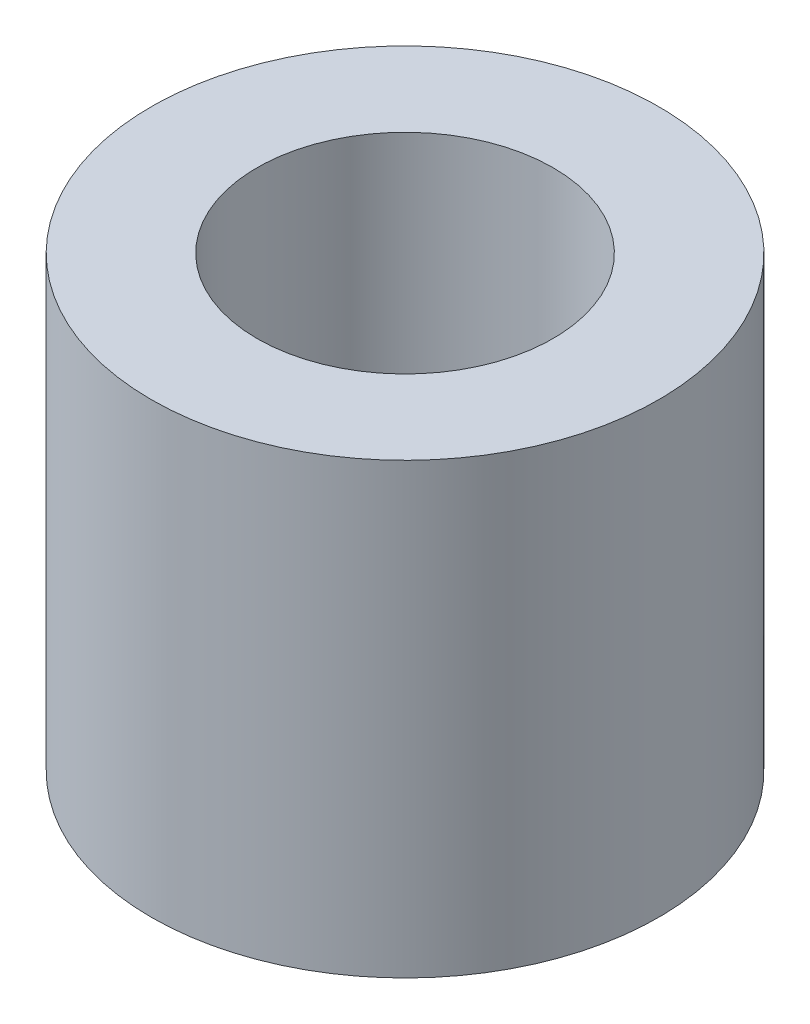
SolidWorks part; units mm, degrees
ref_plane "前视基准面" through (0, 0, 0) normal (0, 0, 1) x (1, 0, 0)
ref_plane "上视基准面" through (0, 0, 0) normal (0, 1, 0) x (1, 0, 0)
ref_plane "右视基准面" through (0, 0, 0) normal (1, 0, 0) x (0, 0, -1)
sketch "草图1" plane through (0, 0, 0) normal (0, 1, 0) x (1, 0, 0)
  circle A0 centre (0, 0) radius 3
  circle A1 centre (0, 0) radius 1.75
  dimension "D1" = 6
  dimension "D2" = 3.5
extrude "凸台-拉伸1" add sketch "草图1" along normal blind 5.3
